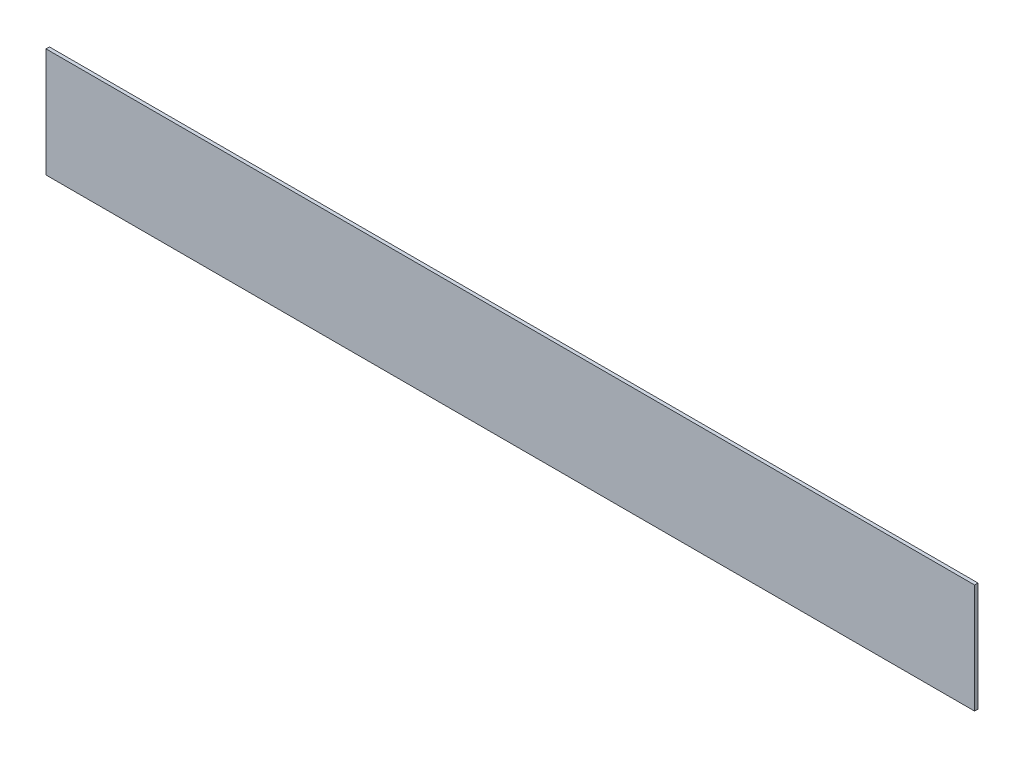
SolidWorks part; units mm, degrees
material "AISI 316 Stainless Steel Sheet (SS)"
ref_plane "Front Plane" through (0, 0, 0) normal (0, 0, 1) x (1, 0, 0)
ref_plane "Top Plane" through (0, 0, 0) normal (0, 1, 0) x (1, 0, 0)
ref_plane "Right Plane" through (0, 0, 0) normal (1, 0, 0) x (0, 0, -1)
sketch "Sketch2" plane through (0, 0, 0) normal (0, 0, 1) x (1, 0, 0)
  line L0 (0, 0) -> (0, 50.8)
  line L1 (0, 50.8) -> (431.8, 50.8)
  line L2 (0, 0) -> (431.8, 0)
  line L3 (431.8, 0) -> (431.8, 50.8)
  dimension "D1" = 431.8
  dimension "D2" = 50.8
extrude "Boss-Extrude1" add sketch "Sketch2" along normal blind 1.5875
